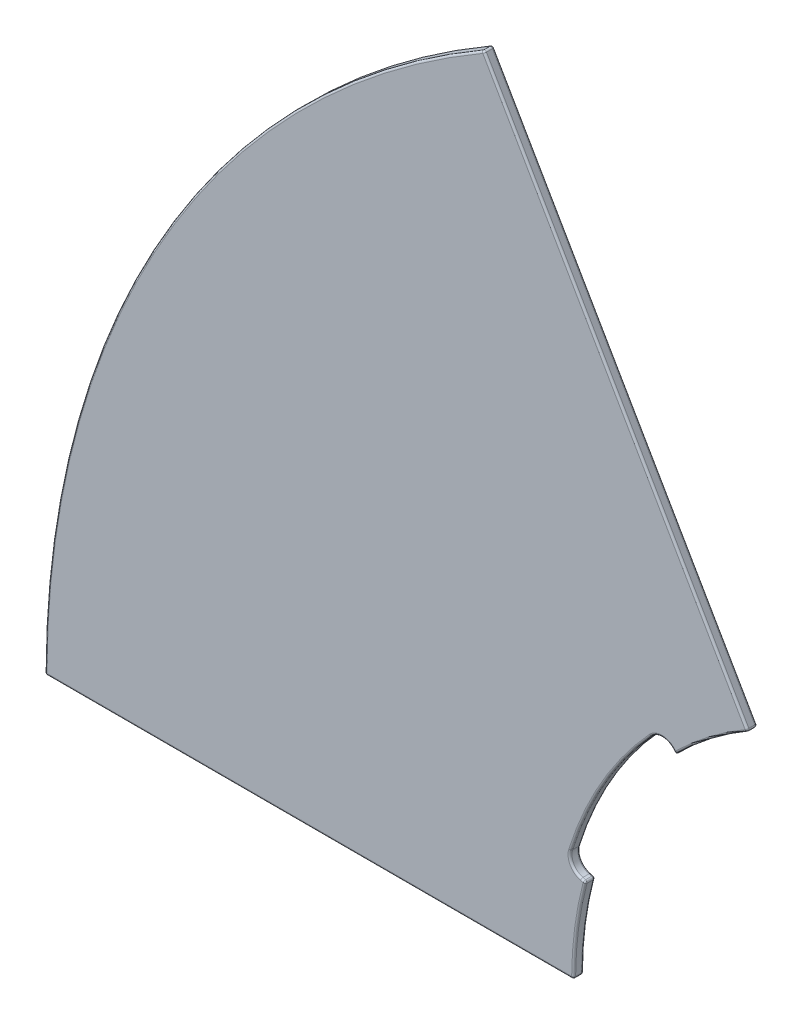
SolidWorks part; units mm, degrees
ref_plane "Front Plane" through (0, 0, 0) normal (0, 0, 1) x (1, 0, 0)
ref_plane "Top Plane" through (0, 0, 0) normal (0, 1, 0) x (1, 0, 0)
ref_plane "Right Plane" through (0, 0, 0) normal (1, 0, 0) x (0, 0, -1)
sketch "Sketch1" plane through (0, 0, 0) normal (0, 0, 1) x (1, 0, 0)
  line L0 (-885.1, 0) -> (-351.6, 0)
  line L2 (0, 0) -> (-529.1079, 916.4417) construction
  line L4 (-442.55, 766.5191) -> (-175.8, 304.4945)
  line L5 (0, 0) -> (-927.2802, 535.3655) construction
  line L9 (-344.1443, 92.2132) -> (-339.6195, 91.0008)
  line L10 (-251.9311, 251.9311) -> (-248.6187, 248.6187)
  arc A0 (-885.1, 0) -> (-442.55, 766.5191) centre (0, 0) cw
  arc A1 (-351.6, 0) -> (-339.6195, 91.0008) centre (0, 0) cw
  arc A5 (-354.5748, 111.1904) -> (-273.5811, 251.4756) centre (0, 0) cw
  arc A6 (-273.5811, 251.4756) -> (-251.9311, 251.9311) centre (-262.5377, 241.3245) cw
  arc A7 (-354.5748, 111.1904) -> (-344.1443, 92.2132) centre (-340.262, 106.7021) ccw
  arc A8 (-248.6187, 248.6187) -> (-175.8, 304.4945) centre (0, 0) cw
  point P3 (0, 0)
  point P17 (-615.7452, 658.5897)
  dimension "D1" = 351.6
  dimension "D2" = 885.1
  dimension "D7" = 15
  dimension "D5" = 20
  dimension "D8" = 15
  dimension "D3" = 60
  dimension "D4" = 30
  dimension "D6" = 15
extrude "Boss-Extrude1" add sketch "Sketch1" along normal blind 10
fillet "Fillet2" radius 2 25 edges at (-885.1, 0, 5) (-442.55, 766.5191, 5) (-351.6, 0, 5) (-618.35, 0, 0) (-348.592, 45.893, 0) (-309.175, 535.5068, 0) (-766.5191, 442.55, 0) (-309.175, 535.5068, 10) (-348.592, 45.893, 10) (-618.35, 0, 10) (-766.5191, 442.55, 10) (-353.4073, 99.477, 0) (-353.4073, 99.477, 10) (-175.8, 304.4945, 5) (-339.6195, 91.0008, 5) (-341.8819, 91.607, 0) (-321.815, 185.8, 0) (-262.8533, 256.3212, 0) (-250.2749, 250.2749, 0) (-214.0405, 278.943, 0) (-214.0405, 278.943, 10) (-250.2749, 250.2749, 10) (-262.8533, 256.3212, 10) (-321.815, 185.8, 10) (-341.8819, 91.607, 10)
sketch "Sketch2" plane through (0, 0, 0) normal (0, 0, -1) x (-1, 0, 0)
  line L4 (0, 0) -> (1533.0382, 885.1) construction
  line L5 (176.7972, 306.2217) -> (441.5489, 764.7851) construction
  line L6 (838.8182, 317.3242) -> (725.5231, 513.5571) construction
  circle A0 centre (746.4617, 448.2904) radius 3.3
  arc A1 (885.0977, 2.0045) -> (444.2848, 765.5149) centre (0, 0) ccw construction
  circle A2 centre (761.4617, 422.3096) radius 3.3
  arc A4 (885.0977, 2.0045) -> (444.2848, 765.5149) centre (0, 0) ccw construction
  point P15 (0, 0)
  point P20 (766.5191, 442.55)
  dimension "D4" = 6.6
  dimension "D5" = 6.6
  dimension "D1" = 30
  dimension "D2" = 15
  dimension "D3" = 15
  dimension "D6" = 14.5
  dimension "D7" = 14.5
extrude "Cut-Extrude1" cut sketch "Sketch2" against normal blind 5
